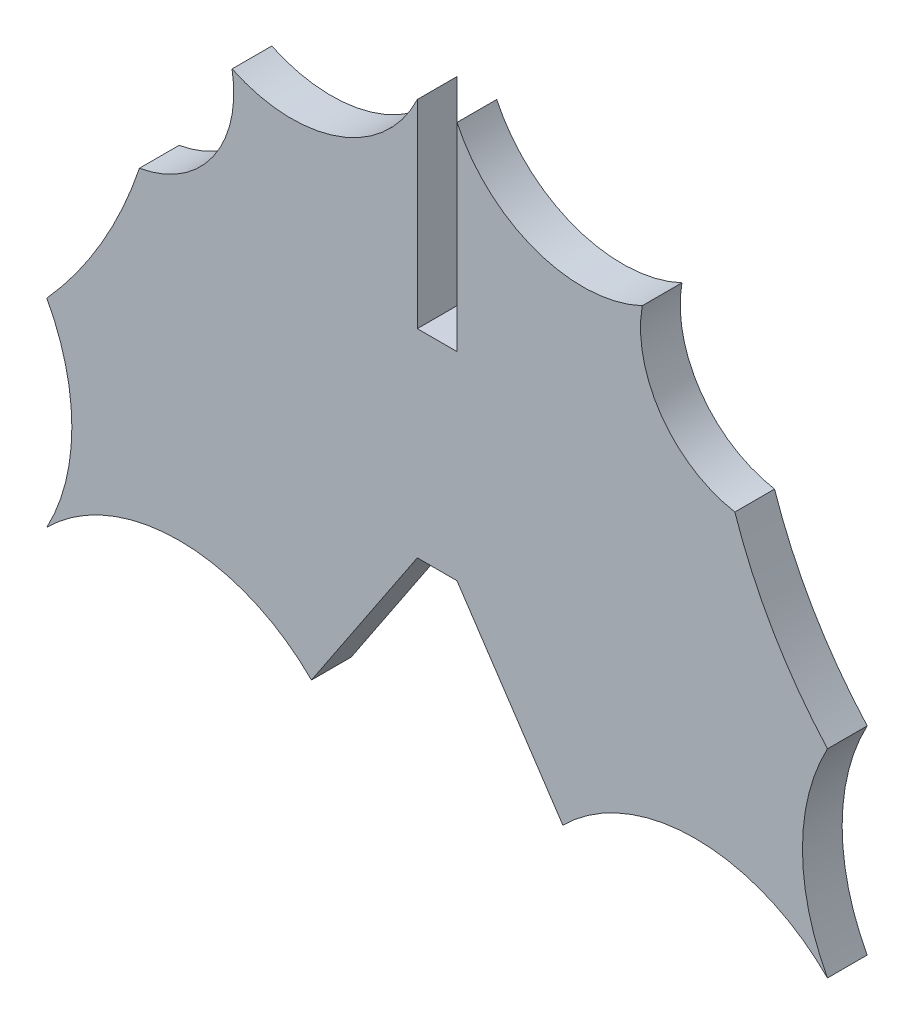
SolidWorks part; units mm, degrees
ref_plane "Alzado" through (0, 0, 0) normal (0, 0, 1) x (1, 0, 0)
ref_plane "Planta" through (0, 0, 0) normal (0, 1, 0) x (1, 0, 0)
ref_plane "Vista lateral" through (0, 0, 0) normal (1, 0, 0) x (0, 0, -1)
sketch "Croquis1" plane through (0, 0, 0) normal (0, 0, 1) x (1, 0, 0)
  line L0 (-2.2624, -14.3773) -> (-18.0166, -14.3773) construction
  line L1 (-10.0166, 12.6227) -> (-7.0166, 12.6227)
  line L2 (-10.0166, 12.6227) -> (-10.0166, -2.3773)
  line L3 (-10.0166, -2.3773) -> (-7.0166, -2.3773)
  line L4 (-7.0166, 12.6227) -> (-7.0166, -2.3773)
  line L5 (-8.5166, -2.3773) -> (-8.5166, 27.6227) construction
  line L6 (-7.0166, 27.6227) -> (-7.0166, -2.3773)
  line L7 (-10.0166, -2.3773) -> (-18.0166, -14.3773)
  line L12 (-18.0166, -14.3773) -> (-38.0166, -14.3773) construction
  line L13 (-38.0166, -14.3773) -> (-38.0166, 0.6227) construction
  line L14 (-38.0166, 0.6227) -> (-38.0166, 12.6227) construction
  line L15 (-38.0166, 12.6227) -> (-31.0166, 12.6227) construction
  line L16 (-31.0166, 12.6227) -> (-31.0166, 22.6227) construction
  line L17 (-31.0166, 22.6227) -> (-24.0166, 22.6227) construction
  line L18 (-24.0166, 22.6227) -> (-24.0166, 27.6227) construction
  line L19 (-24.0166, 27.6227) -> (-10.0166, 27.6227) construction
  line L20 (-10.0166, 27.6227) -> (-10.0166, -2.3773)
  line L21 (-7.0166, -2.3773) -> (0.9834, -14.3773)
  line L22 (-7.0166, 12.6227) -> (-10.0166, 12.6227)
  line L23 (-7.0166, 12.6227) -> (-7.0166, 27.6227)
  line L24 (-7.0166, 27.6227) -> (-10.0166, 27.6227)
  line L25 (-10.0166, 12.6227) -> (-10.0166, 27.6227)
  arc A0 (-38.0166, -14.3773) -> (-18.0166, -14.3773) centre (-28.0166, -24.3773) cw
  arc A1 (-38.0166, -14.3773) -> (-38.0166, 0.6227) centre (-51.9344, -6.8773) ccw
  arc A2 (-38.0166, 0.6227) -> (-31.0166, 12.6227) centre (-63.4675, 23.5107) ccw
  arc A3 (-31.0166, 12.6227) -> (-24.0166, 22.6227) centre (-32.5166, 21.1227) ccw
  arc A4 (-24.0166, 22.6227) -> (-10.0166, 27.6227) centre (-19.5166, 32.1227) ccw
  arc A5 (6.9834, 22.6227) -> (-7.0166, 27.6227) centre (2.4834, 32.1227) cw
  arc A6 (13.9834, 12.6227) -> (6.9834, 22.6227) centre (15.4834, 21.1227) cw
  arc A7 (20.9834, 0.6227) -> (13.9834, 12.6227) centre (46.4342, 23.5107) cw
  arc A8 (20.9834, -14.3773) -> (20.9834, 0.6227) centre (34.9012, -6.8773) cw
  arc A9 (20.9834, -14.3773) -> (0.9834, -14.3773) centre (10.9834, -24.3773) ccw
  point P32 (-7.083, -2.2778)
  point P33 (0.9834, -14.3773)
  point P34 (0, 0)
  dimension "D1" = 15
  dimension "D2" = 3
  dimension "D3" = 20
  dimension "D6" = 15
  dimension "D7" = 15
  dimension "D8" = 12
  dimension "D9" = 7
  dimension "D10" = 10
  dimension "D11" = 7
  dimension "D12" = 5
  dimension "D13" = 14
extrude "Saliente-Extruir2" add sketch "Croquis1" along normal blind 3 contours A9 A8 A7 A6 A5 L6 L4 L21 | L7 A0 A1 A2 A3 A4 L20
